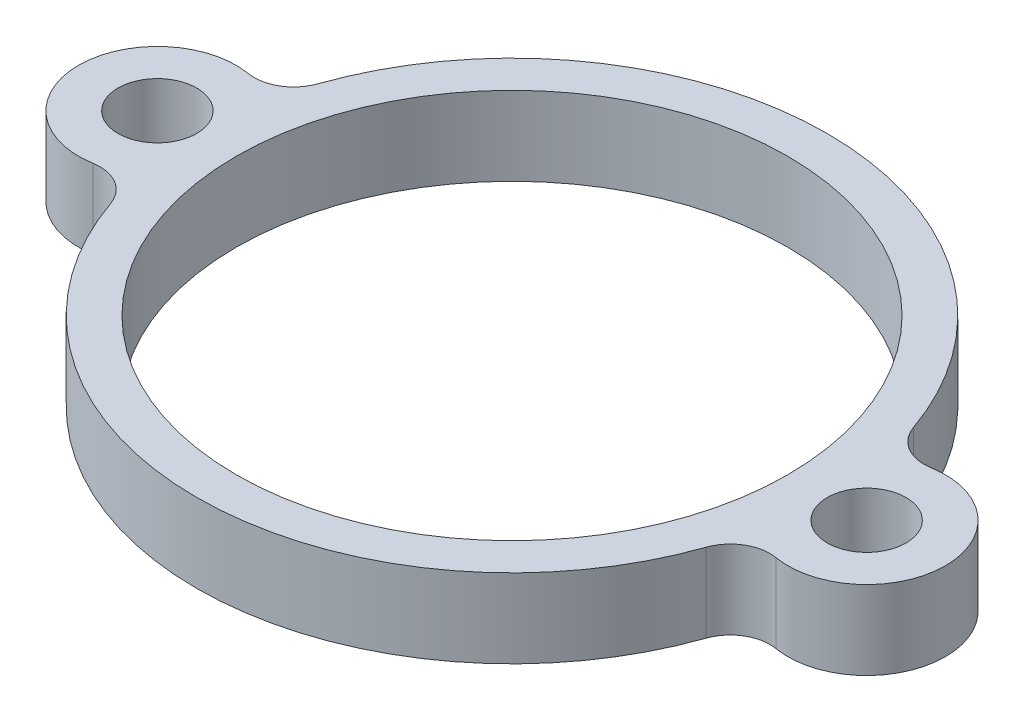
SolidWorks part; units mm, degrees
ref_plane "Front Plane" through (0, 0, 0) normal (0, 0, 1) x (1, 0, 0)
ref_plane "Top Plane" through (0, 0, 0) normal (0, 1, 0) x (1, 0, 0)
ref_plane "Right Plane" through (0, 0, 0) normal (1, 0, 0) x (0, 0, -1)
sketch "Sketch1" plane through (0, 0, 0) normal (0, 1, 0) x (1, 0, 0)
  line L0 (0, 0) -> (45, 0) construction
  line L1 (0, 0) -> (-45, 0) construction
  circle A0 centre (0, 0) radius 35
  circle A1 centre (-45, 0) radius 5
  circle A2 centre (45, 0) radius 5
  arc A3 (-37.7778, -13.1468) -> (37.7778, -13.1468) centre (0, 0) ccw
  arc A4 (-43.3333, 9.8601) -> (-43.3333, -9.8601) centre (-45, 0) ccw
  arc A5 (43.3333, -9.8601) -> (43.3333, 9.8601) centre (45, 0) ccw
  arc A6 (37.7778, 13.1468) -> (-37.7778, 13.1468) centre (0, 0) ccw
  circle A7 centre (-45, 0) radius 10 construction
  circle A8 centre (0, 0) radius 40 construction
  circle A9 centre (45, 0) radius 10 construction
  arc A10 (43.3333, -9.8601) -> (37.7778, -13.1468) centre (42.5, -14.7902) ccw
  arc A11 (43.3333, 9.8601) -> (37.7778, 13.1468) centre (42.5, 14.7902) cw
  arc A12 (-43.3333, 9.8601) -> (-37.7778, 13.1468) centre (-42.5, 14.7902) ccw
  arc A13 (-43.3333, -9.8601) -> (-37.7778, -13.1468) centre (-42.5, -14.7902) cw
  point P8 (70, 0)
  point P13 (-50, 0)
  point P15 (55, 0)
  point P24 (39.1667, -8.1223)
  dimension "D1" = 70
  dimension "D3" = 10
  dimension "D5" = 5
  dimension "D2" = 45
  dimension "D4" = 5
extrude "Boss-Extrude1" add sketch "Sketch1" along normal blind 10
